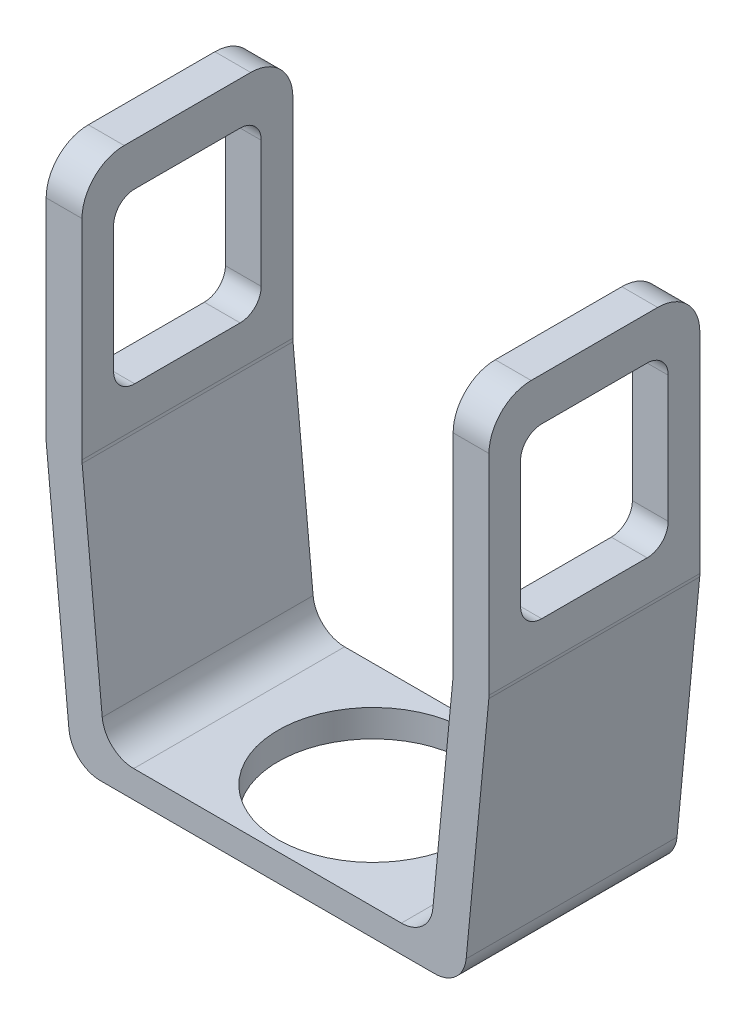
SolidWorks part; units mm, degrees
material "BUTYL"
ref_plane "Alzado" through (0, 0, 0) normal (0, 0, 1) x (1, 0, 0)
ref_plane "Planta" through (0, 0, 0) normal (0, 1, 0) x (1, 0, 0)
ref_plane "Vista lateral" through (0, 0, 0) normal (1, 0, 0) x (0, 0, -1)
sketch "Croquis1" plane through (0, 0, 0) normal (0, 0, 1) x (1, 0, 0)
  line L0 (0, 0) -> (0, 18.6567) construction
  line L1 (-8.8, 24.6521) -> (-10.5, 24.6521)
  line L2 (-10.5, 24.6521) -> (-10.5, 12.7238)
  line L3 (-10.4932, 12.5807) -> (-9.4179, 1.357)
  line L4 (-7.9248, 0) -> (7.9248, 0)
  line L5 (-8.8, 24.6521) -> (-8.8, 12.7396)
  line L6 (-8.7932, 12.5965) -> (-7.84, 2.647)
  line L7 (-6.3468, 1.29) -> (6.3468, 1.29)
  line L8 (8.7932, 12.5965) -> (7.84, 2.647)
  line L9 (10.4932, 12.5807) -> (9.4179, 1.357)
  line L10 (10.5, 24.6521) -> (10.5, 12.7238)
  line L11 (8.8, 24.6521) -> (10.5, 24.6521)
  line L12 (8.8, 24.6521) -> (8.8, 12.7396)
  arc A0 (-7.9248, 0) -> (-9.4179, 1.357) centre (-7.9248, 1.5) cw
  arc A1 (-6.3468, 1.29) -> (-7.84, 2.647) centre (-6.3468, 2.79) cw
  arc A2 (-10.4932, 12.5807) -> (-10.5, 12.7238) centre (-9, 12.7238) cw
  arc A3 (-8.7932, 12.5965) -> (-8.8, 12.7396) centre (-7.3, 12.7396) cw
  arc A4 (8.7932, 12.5965) -> (8.8, 12.7396) centre (7.3, 12.7396) ccw
  arc A5 (10.4932, 12.5807) -> (10.5, 12.7238) centre (9, 12.7238) ccw
  arc A6 (6.3468, 1.29) -> (7.84, 2.647) centre (6.3468, 2.79) ccw
  arc A7 (7.9248, 0) -> (9.4179, 1.357) centre (7.9248, 1.5) ccw
  point P12 (-9.2879, 0)
  point P15 (-7.71, 1.29)
  point P18 (-10.5, 12.6521)
  point P21 (-8.8, 12.6679)
  point P23 (0, 1.29)
  point P34 (8.8, 12.6679)
  point P35 (10.5, 12.6521)
  point P36 (7.71, 1.29)
  point P37 (9.2879, 0)
  dimension "D8" = 1.5
  dimension "D1" = 1.7
  dimension "D2" = 8.8
  dimension "D3" = 12
  dimension "D4" = 12.71
  dimension "D5" = 11.43
  dimension "D6" = 7.71
  dimension "D7" = 1.29
extrude "Saliente-Extruir1" add sketch "Croquis1" along normal mid plane 10
sketch "Croquis2" plane through (0, 0, 0) normal (0, -1, 0) x (1, 0, 0)
  circle A0 centre (0, 0) radius 4.5
  dimension "D1" = 9
extrude "Cortar-Extruir1" cut sketch "Croquis2" against normal through all
sketch "Croquis3" plane through (10.5, 0, 0) normal (1, 0, 0) x (0, 0, -1)
  line L0 (-5, 24.6521) -> (5, 12.5807) construction
  line L2 (-3.5, 22.6164) -> (3.5, 22.6164)
  line L3 (-3.5, 22.6164) -> (-3.5, 14.6164)
  line L4 (-3.5, 14.6164) -> (3.5, 14.6164)
  line L5 (3.5, 22.6164) -> (3.5, 14.6164)
  line L6 (-3.5, 22.6164) -> (3.5, 14.6164) construction
  line L7 (-3.5, 14.6164) -> (3.5, 22.6164) construction
  point P0 (0, 18.6164)
  dimension "D1" = 8
  dimension "D2" = 7
extrude "Cortar-Extruir2" cut sketch "Croquis3" against normal through all
fillet "Redondeo1" radius 2 4 edges at (9.65, 24.6521, -5) (9.65, 24.6521, 5) (-9.65, 24.6521, 5) (-9.65, 24.6521, -5)
fillet "Redondeo2" radius 1 8 edges at (9.65, 22.6164, -3.5) (9.65, 22.6164, 3.5) (9.65, 14.6164, 3.5) (9.65, 14.6164, -3.5) (-9.65, 14.6164, -3.5) (-9.65, 22.6164, 3.5) (-9.65, 22.6164, -3.5) (-9.65, 14.6164, 3.5)
